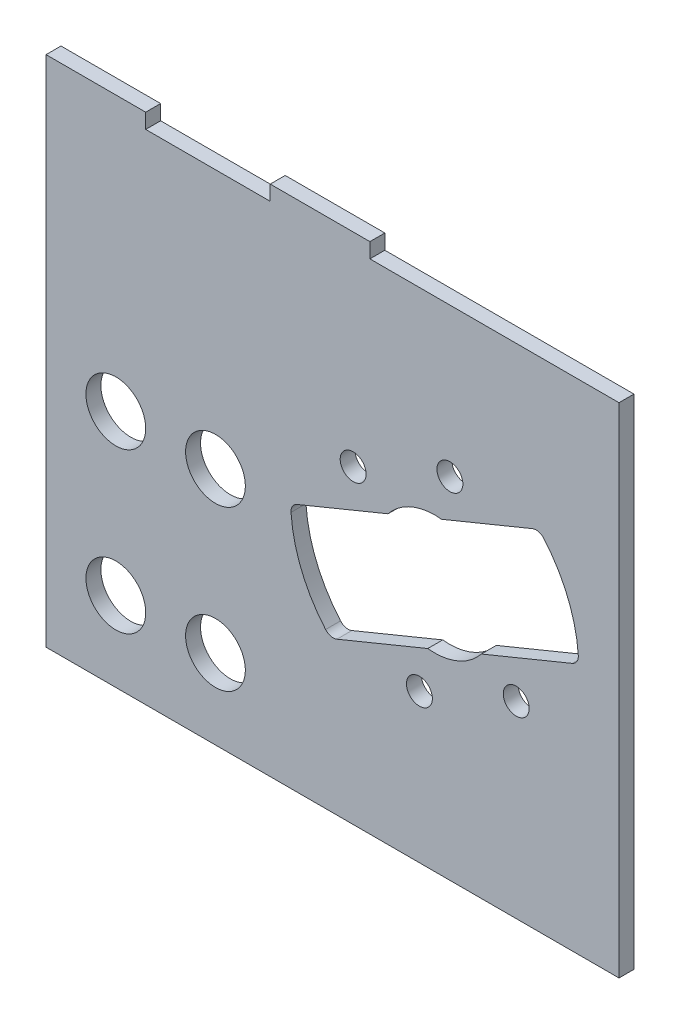
SolidWorks part; units mm, degrees
ref_plane "Front Plane" through (0, 0, 0) normal (0, 0, 1) x (1, 0, 0)
ref_plane "Top Plane" through (0, 0, 0) normal (0, 1, 0) x (1, 0, 0)
ref_plane "Right Plane" through (0, 0, 0) normal (1, 0, 0) x (0, 0, -1)
sketch "Sketch1" plane through (0, 0, 0) normal (0, 0, 1) x (1, 0, 0)
  line L1 (-56.5, 50) -> (58.5, 50)
  line L2 (-56.5, 50) -> (-56.5, -50)
  line L3 (-56.5, -50) -> (58.5, -50)
  line L4 (58.5, 50) -> (58.5, -50)
  line L5 (58.5, 50) -> (15.8909, 50)
  line L9 (-56.5, 50) -> (-36.5, 50)
  line L10 (-56.5, 50) -> (-56.5, 53)
  line L11 (-56.5, 53) -> (-36.5, 53)
  line L12 (-36.5, 50) -> (-36.5, 53)
  line L13 (-11.5, 50) -> (8.5, 50)
  line L14 (-11.5, 50) -> (-11.5, 53)
  line L15 (-11.5, 53) -> (8.5, 53)
  line L16 (8.5, 50) -> (8.5, 53)
  dimension "D2" = 100
  dimension "D3" = 50
  dimension "D4" = 56.5
  dimension "D5" = 3
  dimension "D6" = 25
  dimension "D7" = 20
  dimension "D8" = 115
  dimension "D9" = 20
  dimension "D11" = 3
extrude "Boss-Extrude1" add sketch "Sketch1" along normal blind 3
sketch "Sketch2" plane through (0, 0, 3) normal (0, 0, 1) x (1, 0, 0)
  line L0 (-56.4961, -50) -> (-56.4961, 50) construction
  line L3 (-56.5, -50) -> (58.5, -50) construction
  circle A0 centre (-42.4961, -34) radius 6
  circle A1 centre (-42.4961, -2) radius 6
  circle A2 centre (-22.4961, -34) radius 6
  circle A3 centre (-22.4961, -2) radius 6
  dimension "D1" = 12
  dimension "D2" = 12
  dimension "D3" = 20
  dimension "D5" = 8
  dimension "D6" = 20
  dimension "D7" = 8
  dimension "D8" = 10
extrude "Cut-Extrude1" cut sketch "Sketch2" against normal blind 3
sketch "Sketch3" plane through (0, 0, 3) normal (0, 0, 1) x (1, 0, 0)
  line L0 (-56.5, -50) -> (58.5, -50) construction
  line L2 (58.5, 50) -> (58.5, -50) construction
  line L4 (12.1355, 7.5037) -> (-6.0973, 0.011)
  line L5 (41.1049, 19.4079) -> (22.8696, 11.9216)
  line L6 (30.8645, -7.5037) -> (49.0971, -0.0105)
  line L7 (1.8849, -19.4128) -> (20.1176, -11.9201)
  line L8 (24.5601, 20.1776) -> (5.1363, 12.1955) construction
  line L9 (5.1363, 12.1955) -> (18.4399, -20.1776) construction
  line L10 (18.4399, -20.1776) -> (37.8637, -12.1955) construction
  line L11 (14.8482, 16.1865) -> (28.1518, -16.1865) construction
  circle A2 centre (21.5, 0) radius 32.5 construction
  arc A3 (22.8696, 11.9216) -> (12.1355, 7.5037) centre (21.5, 0) ccw
  arc A4 (43.3898, 18.8683) -> (41.1049, 19.4079) centre (41.8753, 17.5629) ccw
  arc A5 (50.3318, 1.9755) -> (43.3898, 18.8683) centre (21.5, 0) ccw
  arc A6 (49.0971, -0.0105) -> (50.3318, 1.9755) centre (48.3371, 1.8388) ccw
  arc A7 (20.1176, -11.9201) -> (30.8645, -7.5037) centre (21.5, 0) ccw
  arc A8 (-0.3902, -18.8687) -> (1.8849, -19.4128) centre (1.1247, -17.5629) ccw
  arc A9 (-7.3324, -1.9756) -> (-0.3902, -18.8687) centre (21.5, 0) ccw
  arc A10 (-6.0973, 0.011) -> (-7.3324, -1.9756) centre (-5.3371, -1.8388) ccw
  circle A11 centre (18.4399, -20.1776) radius 2.6
  circle A12 centre (37.8637, -12.1955) radius 2.6
  circle A13 centre (5.1363, 12.1955) radius 2.6
  circle A14 centre (24.5601, 20.1776) radius 2.6
  dimension "D7" = 32.5
  dimension "D8" = 12
  dimension "D9" = 12
  dimension "D2" = 50
  dimension "D3" = 37
  dimension "D10" = 35
  dimension "D11" = 21
  dimension "D12" = 21
  dimension "D13" = 35
  dimension "D14" = 19.7123
  dimension "D15" = 19.7123
  dimension "D16" = 19.7123
extrude "Cut-Extrude2" cut sketch "Sketch3" against normal blind 10 contours A14 | A12 | L7 A7 L6 A6 A5 A4 L5 A3 L4 A10 A9 A8 | A11 | A13
